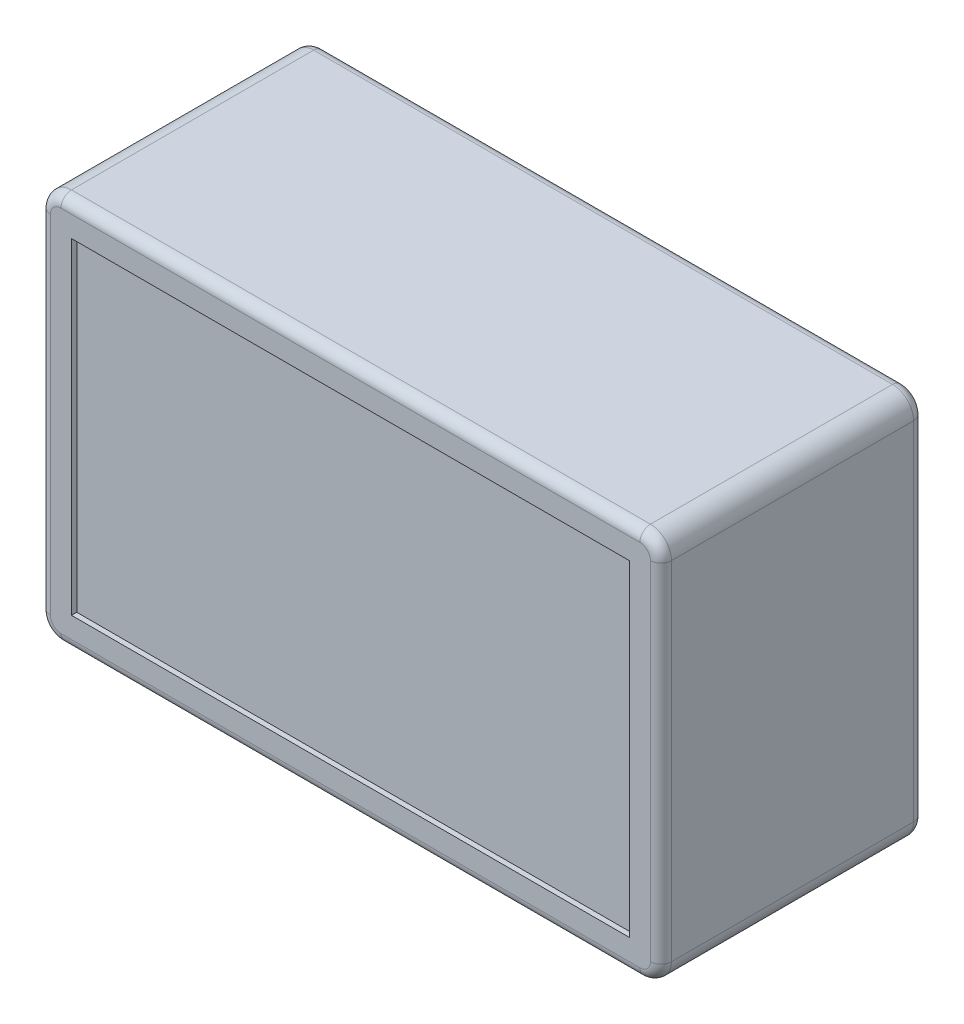
SolidWorks part; units mm, degrees
ref_plane "Front Plane" through (0, 0, 0) normal (0, 0, 1) x (1, 0, 0)
ref_plane "Top Plane" through (0, 0, 0) normal (0, 1, 0) x (1, 0, 0)
ref_plane "Right Plane" through (0, 0, 0) normal (1, 0, 0) x (0, 0, -1)
sketch "Sketch1" plane through (0, 0, 0) normal (0, 0, 1) x (1, 0, 0)
  line L0 (0, 25) -> (0, 97.309) construction
  line L1 (-29.5, 82) -> (29.5, 82)
  line L2 (-29.5, 82) -> (-29.5, 45)
  line L3 (-29.5, 45) -> (29.5, 45)
  line L4 (29.5, 82) -> (29.5, 45)
  point P8 (0, 0)
  dimension "D1" = 59
  dimension "D2" = 37
  dimension "D3" = 29.5
  dimension "D4" = 45
extrude "Boss-Extrude1" add sketch "Sketch1" along normal mid plane 25
sketch "Sketch2" plane through (0, 0, -12.5) normal (0, 0, -1) x (-1, 0, 0)
  line L0 (29.5, 63.5) -> (-29.5, 63.5) construction
  line L1 (29.5, 82) -> (29.5, 45) construction
  line L2 (-29.5, 45) -> (-29.5, 82) construction
  circle A0 centre (14.5, 66.5) radius 7
  point P8 (0, 0)
extrude "Boss-Extrude2" add sketch "Sketch2" along normal blind 3
fillet "Fillet1" radius 2 4 edges at (29.5, 45, 0) (29.5, 82, 0) (-29.5, 45, 0) (-29.5, 82, 0)
sketch "Sketch3" plane through (0, 0, -12.5) normal (0, 0, -1) x (-1, 0, 0)
  line L1 (5.5, 78.5) -> (23.5, 78.5)
  line L2 (2.5, 75.5) -> (2.5, 57.5)
  line L3 (5.5, 54.5) -> (23.5, 54.5)
  line L4 (26.5, 75.5) -> (26.5, 57.5)
  circle A0 centre (14.5, 66.5) radius 7 construction
  arc A1 (23.5, 78.5) -> (26.5, 75.5) centre (23.5, 75.5) cw
  arc A2 (23.5, 54.5) -> (26.5, 57.5) centre (23.5, 57.5) ccw
  arc A3 (2.5, 57.5) -> (5.5, 54.5) centre (5.5, 57.5) ccw
  arc A4 (5.5, 78.5) -> (2.5, 75.5) centre (5.5, 75.5) ccw
  point P8 (26.5, 78.5)
  point P11 (26.5, 54.5)
  point P16 (2.5, 78.5)
  dimension "D5" = 3
  dimension "D1" = 12
  dimension "D2" = 24
  dimension "D3" = 24
  dimension "D4" = 12
extrude "Boss-Extrude3" add sketch "Sketch3" along normal mid plane 2
sketch "Sketch4" plane through (0, 0, -15.5) normal (0, 0, -1) x (-1, 0, 0)
  circle A0 centre (14.5, 66.5) radius 6
extrude "Cut-Extrude1" cut sketch "Sketch4" against normal blind 0.5
sketch "Sketch5" plane through (0, 0, -12.5) normal (0, 0, -1) x (-1, 0, 0)
  line L0 (-29.5, 63.5) -> (29.5, 63.5) construction
  line L1 (-29.5, 47) -> (-29.5, 80) construction
  line L2 (29.5, 80) -> (29.5, 47) construction
  circle A0 centre (-17.5, 63.5) radius 5
  point P8 (0, 0)
  dimension "D1" = 10
  dimension "D2" = 12
extrude "Boss-Extrude4" add sketch "Sketch5" along normal blind 2
fillet "Fillet2" radius 1 16 edges at (28.9142, 81.4142, 12.5) (29.5, 63.5, 12.5) (28.9142, 45.5858, 12.5) (0, 45, 12.5) (-28.9142, 45.5858, 12.5) (-29.5, 63.5, 12.5) (-28.9142, 81.4142, 12.5) (28.9142, 81.4142, -12.5) (29.5, 63.5, -12.5) (28.9142, 45.5858, -12.5) (0, 45, -12.5) (-28.9142, 45.5858, -12.5) (-29.5, 63.5, -12.5) (-28.9142, 81.4142, -12.5) (0, 82, 12.5) (0, 82, -12.5)
sketch "Sketch6" plane through (0, 0, 12.5) normal (0, 0, 1) x (1, 0, 0)
  line L8 (26.5, 48) -> (26.5, 79)
  line L9 (26.5, 79) -> (-26.5, 79)
  line L10 (-26.5, 79) -> (-26.5, 48)
  line L11 (-26.5, 48) -> (26.5, 48)
  line L12 (26.5, 48) -> (26.5, 79)
  line L13 (26.5, 79) -> (-26.5, 79)
  line L14 (-26.5, 79) -> (-26.5, 48)
  line L15 (-26.5, 48) -> (26.5, 48)
  dimension "D1" = 2
extrude "Cut-Extrude2" cut sketch "Sketch6" against normal blind 0.5
